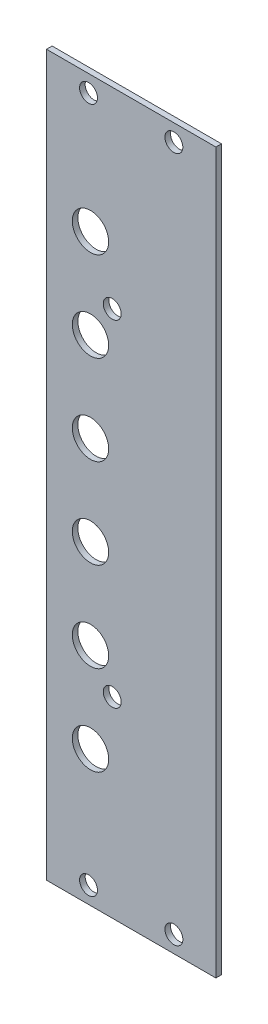
SolidWorks part; units mm, degrees
ref_plane "Front Plane" through (0, 0, 0) normal (0, 0, 1) x (1, 0, 0)
ref_plane "Top Plane" through (0, 0, 0) normal (0, 1, 0) x (1, 0, 0)
ref_plane "Right Plane" through (0, 0, 0) normal (1, 0, 0) x (0, 0, -1)
sketch "Sketch2" plane through (0, 0, 0) normal (0, 0, 1) x (1, 0, 0)
  line L0 (7.5, 125.5) -> (7.5, 128.5) construction
  line L1 (0, 0) -> (30.24, 0)
  line L2 (0, 0) -> (0, 128.5)
  line L3 (0, 128.5) -> (30.24, 128.5)
  line L4 (30.24, 0) -> (30.24, 128.5)
  line L5 (7.5, 125.5) -> (22.74, 125.5) construction
  line L6 (7.5, 125.5) -> (7.5, 3) construction
  line L7 (7.5, 3) -> (22.74, 3) construction
  line L8 (22.74, 125.5) -> (22.74, 3) construction
  line L9 (7.5, 3) -> (7.5, 0) construction
  line L10 (7.5, 125.5) -> (0, 125.5) construction
  line L11 (22.74, 125.5) -> (30.24, 125.5) construction
  circle A0 centre (7.5, 125.5) radius 1.6
  circle A1 centre (22.74, 125.5) radius 1.6
  circle A2 centre (22.74, 3) radius 1.6
  circle A3 centre (7.5, 3) radius 1.6
  dimension "D5" = 3.2
  dimension "D1" = 3
  dimension "D2" = 7.5
  dimension "D3" = 128.5
  dimension "D4" = 15.24
extrude "Boss-Extrude1" add sketch "Sketch2" along normal blind 1 contours L1 L4 L3 L2 A3 A2 A1 A0
sketch "Sketch3" plane through (0, 0, 1) normal (0, 0, 1) x (1, 0, 0)
  line L1 (0, 0) -> (0, 128.5) construction
  line L2 (0, 128.5) -> (30.24, 128.5) construction
  circle A0 centre (7.85, 104.25) radius 3.25
  circle A1 centre (7.85, 88.25) radius 3.25
  circle A2 centre (7.85, 72.25) radius 3.25
  circle A3 centre (7.85, 56.25) radius 3.25
  circle A4 centre (7.85, 40.25) radius 3.25
  circle A5 centre (7.85, 24.25) radius 3.25
  point P0 (7.85, 104.25)
  dimension "D5" = 6.5
  dimension "D1" = 7.85
  dimension "D2" = 24.25
  dimension "D4" = 16
  dimension "D3" = 6
extrude "sma_cuts" cut sketch "Sketch3" against normal through all both and the other way through all
sketch "Sketch4" plane through (0, 0, 1) normal (0, 0, 1) x (1, 0, 0)
  line L0 (0, 0) -> (0, 128.5) construction
  line L1 (0, 128.5) -> (30.24, 128.5) construction
  circle A0 centre (11.7314, 94.225) radius 1.6
  circle A1 centre (11.7314, 34.225) radius 1.6
  dimension "D1" = 60
  dimension "D4" = 3.2
  dimension "D2" = 11.7314
  dimension "D3" = 34.275
extrude "mounting_bracket_cuts" cut sketch "Sketch4" against normal through all both and the other way through all
